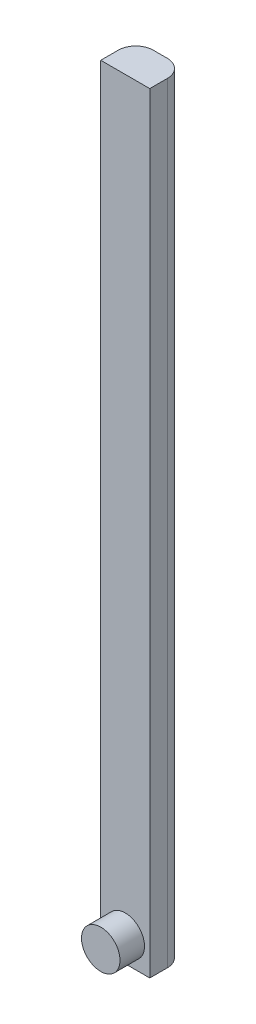
SolidWorks part; units mm, degrees
ref_plane "Front Plane" through (0, 0, 0) normal (0, 0, 1) x (1, 0, 0)
ref_plane "Top Plane" through (0, 0, 0) normal (0, 1, 0) x (1, 0, 0)
ref_plane "Right Plane" through (0, 0, 0) normal (1, 0, 0) x (0, 0, -1)
sketch "Sketch1" plane through (0, 0, 0) normal (0, 0, 1) x (1, 0, 0)
  line L0 (0, 0) -> (7, 0)
  line L1 (7, 0) -> (7, 110)
  line L2 (7, 110) -> (0, 110)
  line L3 (0, 110) -> (0, 0)
extrude "Boss-Extrude1" add sketch "Sketch1" along normal blind 5
fillet "Fillet4" radius 2.5 2 edges at (7, 55, 0) (0, 55, 0)
sketch "Sketch2" plane through (0, 0, 5) normal (0, 0, 1) x (1, 0, 0)
  circle A0 centre (3.5, 3.5489) radius 2.75
extrude "Boss-Extrude2" add sketch "Sketch2" along normal blind 3.5
